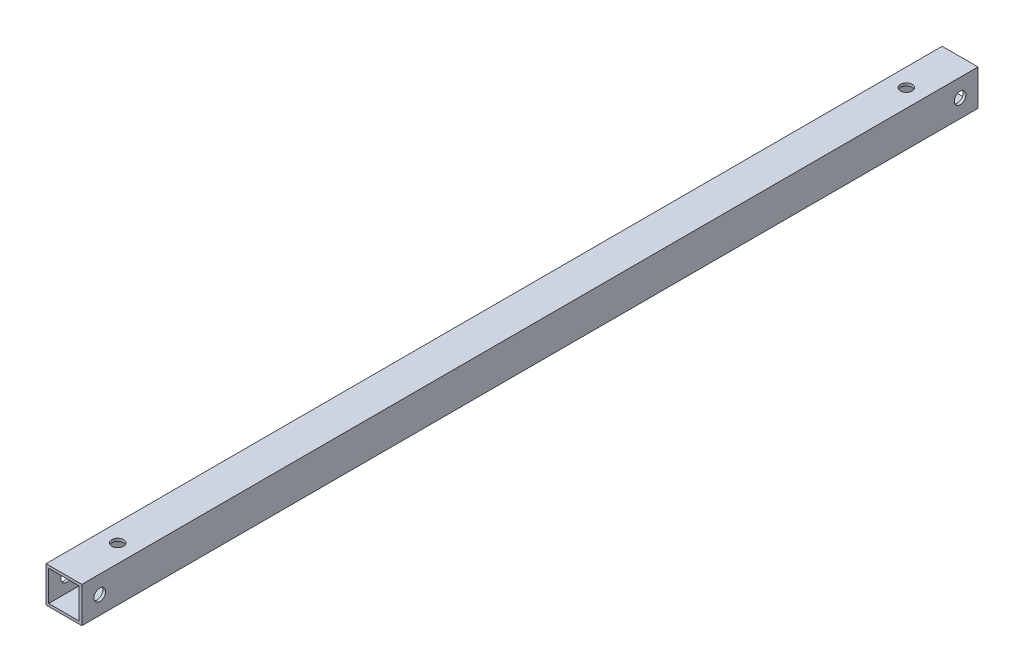
SolidWorks part; units mm, degrees
material "3.0205 (EN AW-1200)"
ref_plane "Ebene vorne" through (0, 0, 0) normal (0, 0, 1) x (1, 0, 0)
ref_plane "Ebene oben" through (0, 0, 0) normal (0, 1, 0) x (1, 0, 0)
ref_plane "Ebene rechts" through (0, 0, 0) normal (1, 0, 0) x (0, 0, -1)
sketch "Skizze1" plane through (0, 0, 0) normal (0, 0, 1) x (1, 0, 0)
  line L1 (10, -10) -> (-10, -10)
  line L2 (10, -10) -> (10, 10)
  line L3 (10, 10) -> (-10, 10)
  line L4 (-10, -10) -> (-10, 10)
  line L5 (10, -10) -> (-10, 10) construction
  line L6 (10, 10) -> (-10, -10) construction
  line L7 (8.5, -8.5) -> (-8.5, -8.5)
  line L8 (8.5, -8.5) -> (8.5, 8.5)
  line L9 (8.5, 8.5) -> (-8.5, 8.5)
  line L10 (-8.5, -8.5) -> (-8.5, 8.5)
  line L11 (8.5, -8.5) -> (-8.5, 8.5) construction
  line L12 (8.5, 8.5) -> (-8.5, -8.5) construction
  point P0 (0, 0)
  point P6 (0, 0)
  dimension "D1" = 20
  dimension "D2" = 1.5
extrude "Aufsatz-Linear austragen1" add sketch "Skizze1" against normal mid plane 500
sketch "Skizze2" plane through (0, 0, 0) normal (0, 1, 0) x (1, 0, 0)
  line L0 (0, -220) -> (0, 220) construction
  line L1 (10, -250) -> (-10, -250) construction
  circle A0 centre (0, -220) radius 3.25
  circle A1 centre (0, 220) radius 3.25
  dimension "D2" = 6.5
  dimension "D1" = 30
extrude "Schnitt-Linear austragen1" cut sketch "Skizze2" against normal mid plane 30
sketch "Skizze3" plane through (0, 0, 0) normal (1, 0, 0) x (0, 0, -1)
  line L0 (-240, 0) -> (240, 0) construction
  line L1 (-250, 10) -> (-250, -10) construction
  circle A0 centre (-240, 0) radius 3.25
  circle A1 centre (240, 0) radius 3.25
  point P2 (-250, 0)
  dimension "D2" = 6.5
  dimension "D3" = 6.5
  dimension "D1" = 10
extrude "Schnitt-Linear austragen2" cut sketch "Skizze3" against normal mid plane 30
